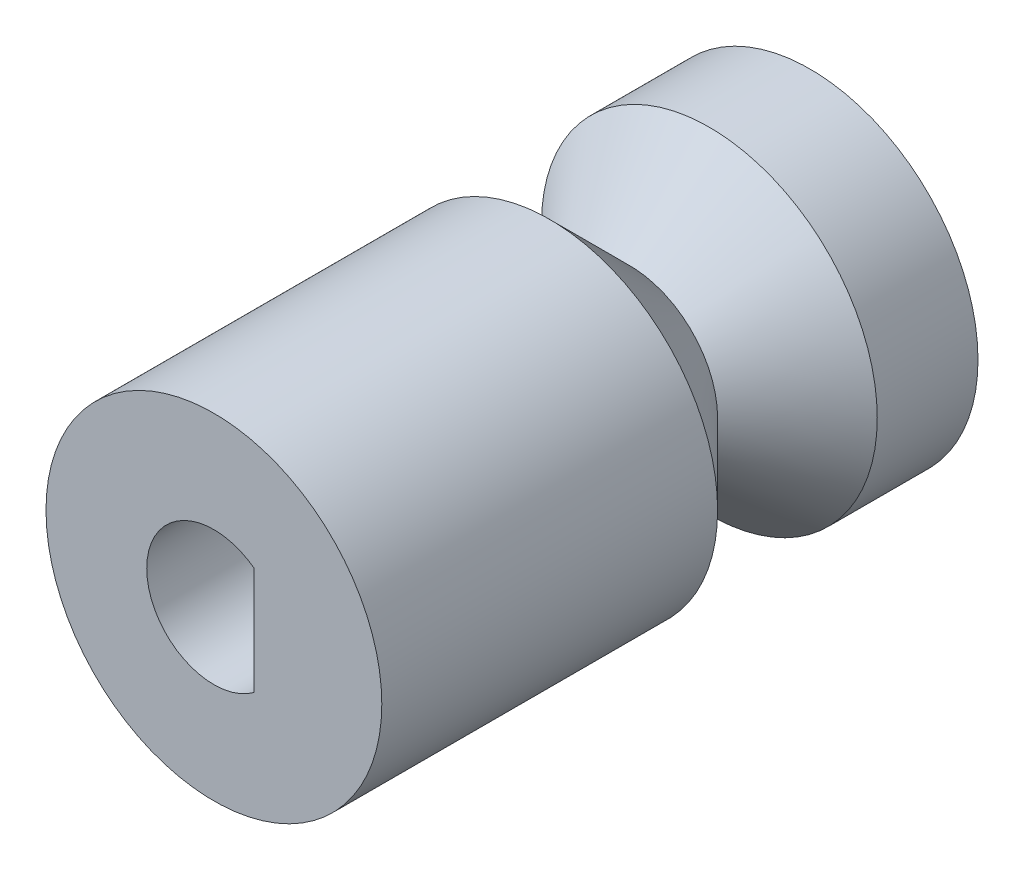
SolidWorks part; units mm, degrees
ref_plane "Plano frontal" through (0, 0, 0) normal (0, 0, 1) x (1, 0, 0)
ref_plane "Plano superior" through (0, 0, 0) normal (0, 1, 0) x (1, 0, 0)
ref_plane "Plano direito" through (0, 0, 0) normal (1, 0, 0) x (0, 0, -1)
sketch "Esboço1" plane through (0, 0, 0) normal (0, 0, 1) x (1, 0, 0)
  line L0 (0, 0) -> (0, 2) construction
  line L1 (0, 0) -> (1.2, 0) construction
  line L3 (1.2, 1.6) -> (1.2, -1.6)
  arc A0 (1.2, 1.6) -> (1.2, -1.6) centre (0, 0) ccw
  circle A1 centre (0, 0) radius 5
  dimension "D1" = 4
extrude "Ressalto-extrusão1" add sketch "Esboço1" along normal blind 10
sketch "Esboço3" plane through (0, 0, 0) normal (0, 1, 0) x (1, 0, 0)
  line L0 (0, 0) -> (0, 6.5523) construction
  line L2 (0, 0) -> (5, 0)
  line L3 (5, 0) -> (2.6229, 2.3771)
  line L4 (2.6229, 2.3771) -> (5, 4.7543)
  line L5 (5, 4.7543) -> (0, 4.7543)
  line L6 (0, 4.7543) -> (0, 0)
  point P2 (0, 0)
  point P5 (1.9884, 3.0116)
  point P9 (2.6229, 2.3771)
  point P10 (-0.4, 0)
  dimension "D1" = 45
  dimension "D2" = 0
revolve "Revolução1" add sketch "Esboço3" angle 360 about L0
sketch "Esboço4" plane through (0, 0, -4.7543) normal (0, 0, -1) x (-1, 0, 0)
  circle A0 centre (0, 0) radius 5
extrude "Ressalto-extrusão3" add sketch "Esboço4" along normal blind 3
